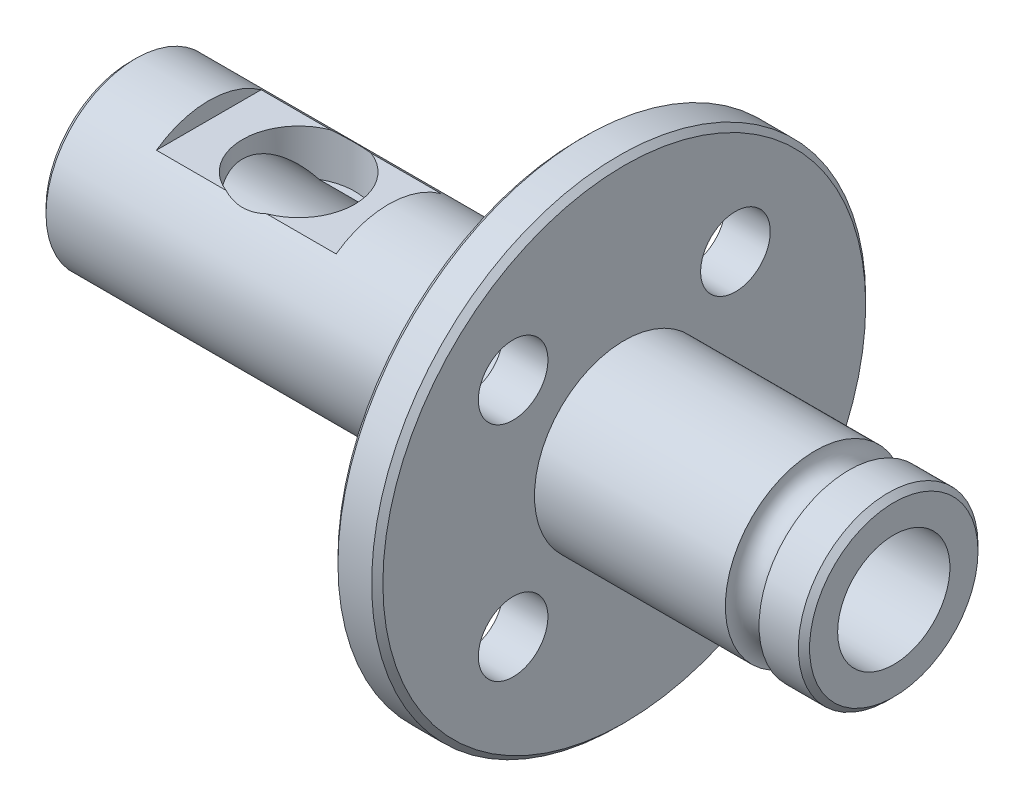
SolidWorks part; units mm, degrees
ref_plane "Front Plane" through (0, 0, 0) normal (0, 0, 1) x (1, 0, 0)
ref_plane "Top Plane" through (0, 0, 0) normal (0, 1, 0) x (1, 0, 0)
ref_plane "Right Plane" through (0, 0, 0) normal (1, 0, 0) x (0, 0, -1)
sketch "Sketch2" plane through (0, 0, 0) normal (0, 0, 1) x (1, 0, 0)
  line L0 (0, 0) -> (0, 4)
  line L1 (0, 4) -> (20, 4)
  line L2 (20, 4) -> (20, 11)
  line L3 (20, 11) -> (22, 11)
  line L4 (22, 11) -> (22, 4)
  line L5 (22, 4) -> (30.5, 4)
  line L6 (34, 4) -> (34, 0)
  line L7 (34, 0) -> (0, 0)
  line L8 (32, 4) -> (34, 4)
  arc A0 (30.5, 4) -> (32, 4) centre (31.25, 4) ccw
  dimension "D7" = 1.5
  dimension "D1" = 34
  dimension "D2" = 4
  dimension "D3" = 20
  dimension "D4" = 7
  dimension "D5" = 7
  dimension "D6" = 2
  dimension "D8" = 2.75
revolve "Revolve1" add sketch "Sketch2" angle 360 about L7
sketch "Sketch3" plane through (22, 0, 0) normal (1, 0, 0) x (0, 0, -1)
  line L0 (-7, 0) -> (7, 0) construction
  line L1 (0, 0) -> (0, 7) construction
  line L2 (0, 0) -> (4.9497, 4.9497) construction
  circle A0 centre (0, 0) radius 7 construction
  circle A1 centre (4.9497, 4.9497) radius 1.55
  circle A2 centre (4.9497, -4.9497) radius 1.55
  circle A3 centre (-4.9497, -4.9497) radius 1.55
  circle A4 centre (-4.9497, 4.9497) radius 1.55
  point P17 (0, 0)
  dimension "D1" = 14
  dimension "D3" = 3.1
  dimension "D2" = 45
  dimension "D4" = 4
extrude "Cut-Extrude1" cut sketch "Sketch3" against normal blind 10
sketch "Sketch4" plane through (0, 0, 0) normal (-1, 0, 0) x (0, 0, 1)
  circle A0 centre (0, 0) radius 2.5
  dimension "D1" = 5
extrude "Cut-Extrude2" cut sketch "Sketch4" against normal through all
ref_plane "Plane1" through (0, 4, 0) normal (0, 1, 0) x (1, 0, 0)
sketch "Sketch6" plane through (0, 4, 0) normal (0, 1, 0) x (1, 0, 0)
  line L0 (0, 0) -> (20, 0) construction
  line L1 (3.5, 2.5) -> (11.5, 2.5)
  line L2 (3.5, 2.5) -> (3.5, -2.5)
  line L3 (3.5, -2.5) -> (11.5, -2.5)
  line L4 (11.5, 2.5) -> (11.5, -2.5)
  line L5 (3.5, 2.5) -> (11.5, -2.5) construction
  line L6 (3.5, -2.5) -> (11.5, 2.5) construction
  line L7 (20, 11) -> (20, -11) construction
  point P0 (7.5, 0)
  point P10 (11.5, 0)
  point P11 (9.5204, 0)
  point P12 (9.5058, 0)
  dimension "D1" = 5
  dimension "D2" = 8
  dimension "D3" = 7.5
extrude "Cut-Extrude4" cut sketch "Sketch6" against normal blind 0.75
sketch "Sketch8" plane through (0, 3.25, 0) normal (0, 1, 0) x (1, 0, 0)
  circle A0 centre (7.5, 0) radius 2.5
  dimension "D1" = 5
  dimension "D2" = 7.5
extrude "Cut-Extrude5" cut sketch "Sketch8" against normal blind 2
chamfer "Chamfer1" distance 0.25 angle 45 4 edges at (34, 0, -4) (22, 0, -11) (20, 0, -11) (0, 0, -4)
